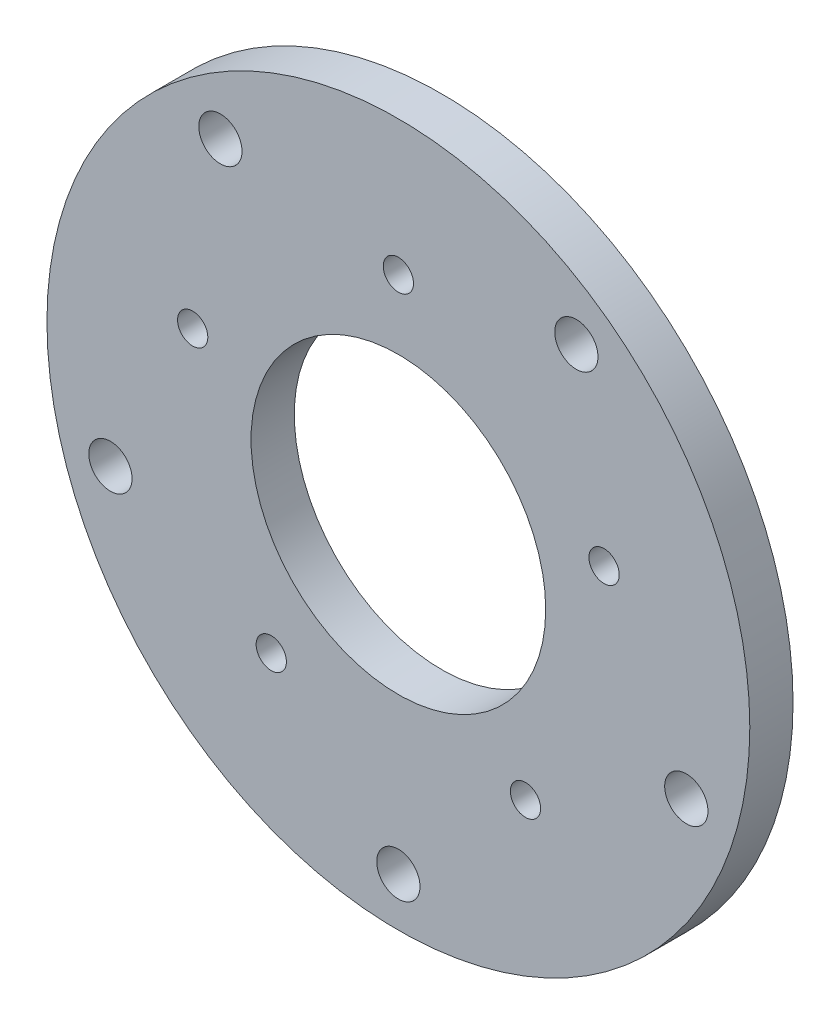
SolidWorks part; units mm, degrees
ref_plane "前视基准面" through (0, 0, 0) normal (0, 0, 1) x (1, 0, 0)
ref_plane "上视基准面" through (0, 0, 0) normal (0, 1, 0) x (1, 0, 0)
ref_plane "右视基准面" through (0, 0, 0) normal (1, 0, 0) x (0, 0, -1)
sketch "草图1" plane through (0, 0, 0) normal (0, 0, 1) x (1, 0, 0)
  line L0 (-26.8908, -7.9995) -> (-0.2612, -27.347) construction
  line L1 (-13.576, -17.6733) -> (-5.2543, -6.2194) construction
  circle A0 centre (-0.2612, 0.653) radius 32.5
  circle A1 centre (-0.2612, 0.653) radius 13.625
  circle A2 centre (-0.2612, -27.347) radius 2
  circle A3 centre (-26.8908, -7.9995) radius 2
  circle A4 centre (-16.7192, 23.3054) radius 2
  circle A5 centre (16.1968, 23.3054) radius 2
  circle A6 centre (26.3684, -7.9995) radius 2
  circle A7 centre (-0.2612, 0.653) radius 20 construction
  circle A8 centre (-12.0169, -15.5274) radius 1.4
  circle A9 centre (-19.2823, 6.8333) radius 1.4
  circle A10 centre (-0.2612, 20.653) radius 1.4
  circle A11 centre (18.7599, 6.8333) radius 1.4
  circle A12 centre (11.4945, -15.5274) radius 1.4
  dimension "D1" = 65
  dimension "D2" = 40
  dimension "D3" = 27.25
  dimension "D4" = 2.8
  dimension "D5" = 5
extrude "凸台-拉伸1" add sketch "草图1" along normal blind 4 contours A0
